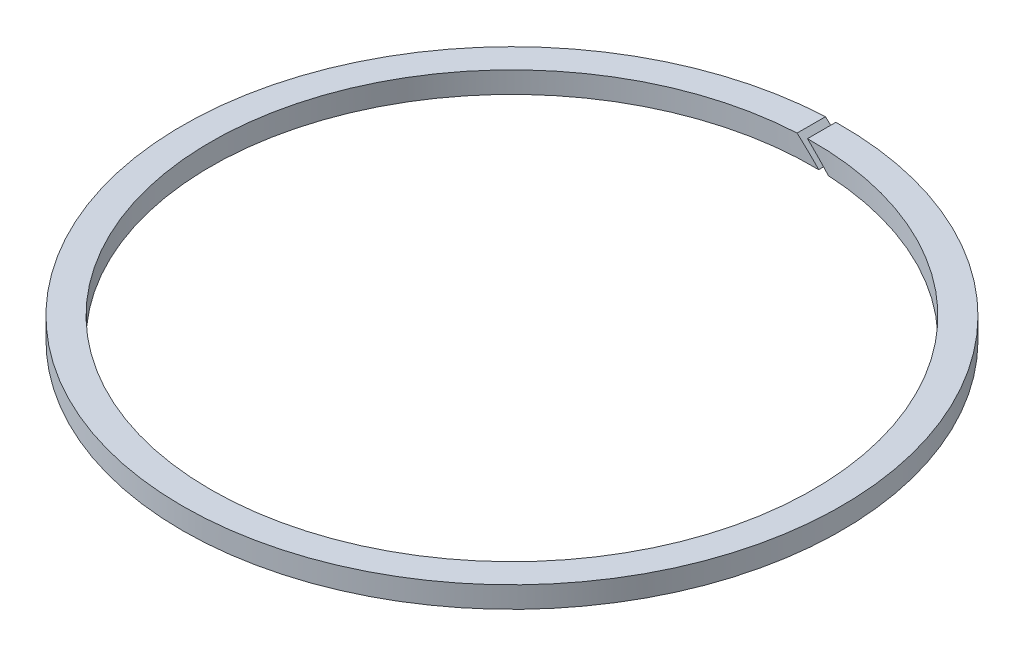
SolidWorks part; units mm, degrees
ref_plane "Front Plane" through (0, 0, 0) normal (0, 0, 1) x (1, 0, 0)
ref_plane "Top Plane" through (0, 0, 0) normal (0, 1, 0) x (1, 0, 0)
ref_plane "Right Plane" through (0, 0, 0) normal (1, 0, 0) x (0, 0, -1)
sketch "Sketch2" plane through (0, 0, 0) normal (0, 1, 0) x (1, 0, 0)
  line L0 (0, 0) -> (0, 20028.5298) construction
  line L1 (0, 0) -> (20028.5298, 0) construction
  circle A0 centre (0, 0) radius 46.5
  circle A1 centre (0, 0) radius 42.5
  dimension "D1" = 93
  dimension "D2" = 85
extrude "Boss-Extrude1" add sketch "Sketch2" along normal mid plane 3
sketch "Sketch3" plane through (0, 0, 0) normal (0, 0, 1) x (1, 0, 0)
  line L0 (0, 0) -> (0, -50000) construction
  line L1 (0, 0) -> (50000, 0) construction
  line L2 (-5.4492, 6.1563) -> (6.1563, -5.4492)
  line L3 (-5.4492, 6.1563) -> (-6.1563, 5.4492)
  line L4 (6.1563, -5.4492) -> (5.4492, -6.1563)
  line L5 (-6.1563, 5.4492) -> (5.4492, -6.1563)
  line L6 (-5.4492, 6.1563) -> (5.4492, -6.1563) construction
  line L7 (6.1563, -5.4492) -> (-6.1563, 5.4492) construction
  point P6 (0, 0)
  dimension "D1" = 45
  dimension "D2" = 1
extrude "Cut-Extrude1" cut sketch "Sketch3" against normal up to next
